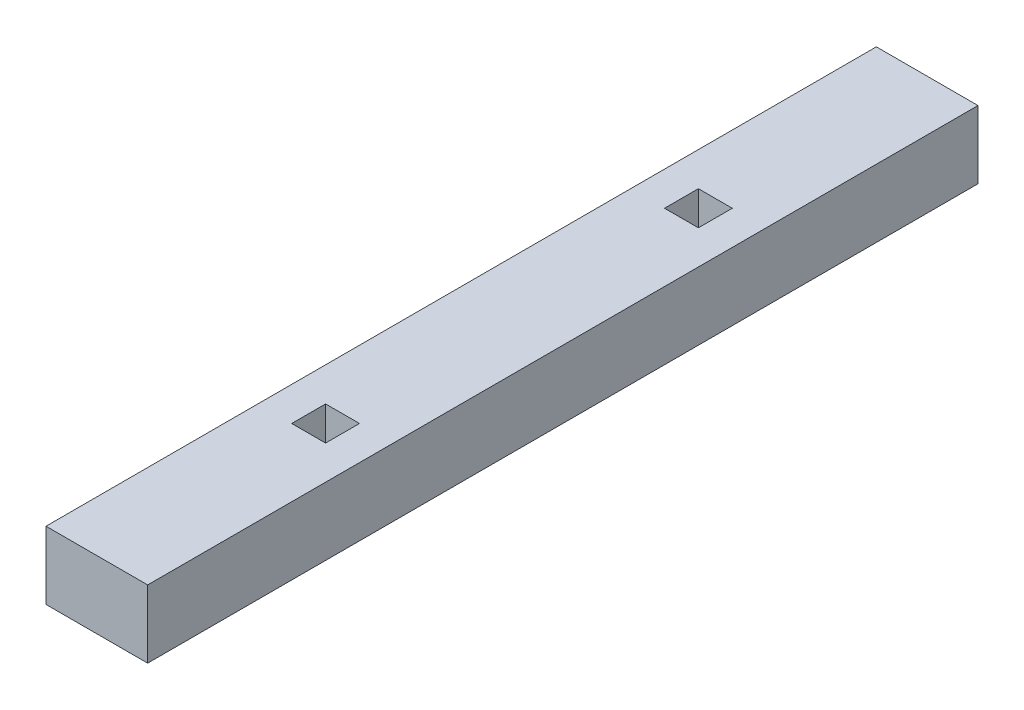
SolidWorks part; units mm, degrees
ref_plane "Front Plane" through (0, 0, 0) normal (0, 0, 1) x (1, 0, 0)
ref_plane "Top Plane" through (0, 0, 0) normal (0, 1, 0) x (1, 0, 0)
ref_plane "Right Plane" through (0, 0, 0) normal (1, 0, 0) x (0, 0, -1)
sketch "Sketch1" plane through (0, 0, 0) normal (0, 1, 0) x (1, 0, 0)
  line L0 (0, 117.5) -> (0, -127.5) construction
  line L1 (-15, 117.5) -> (15, 117.5)
  line L2 (-15, 117.5) -> (-15, -127.5)
  line L3 (-15, -127.5) -> (15, -127.5)
  line L4 (15, 117.5) -> (15, -127.5)
  line L5 (-5, 55) -> (5, 55)
  line L6 (-5, 55) -> (-5, 45)
  line L7 (-5, 45) -> (5, 45)
  line L8 (5, 55) -> (5, 45)
  line L9 (15, -5) -> (-15, -5) construction
  line L10 (-5, -65) -> (-5, -55)
  line L11 (-5, -55) -> (5, -55)
  line L12 (5, -65) -> (5, -55)
  line L13 (-5, -65) -> (5, -65)
  point P9 (0, 55)
  point P10 (0, 117.5)
  dimension "D3" = 10
  dimension "D5" = 100
  dimension "D4" = 10
  dimension "D1" = 30
  dimension "D2" = 245
extrude "Boss-Extrude1" add sketch "Sketch1" along normal blind 20
